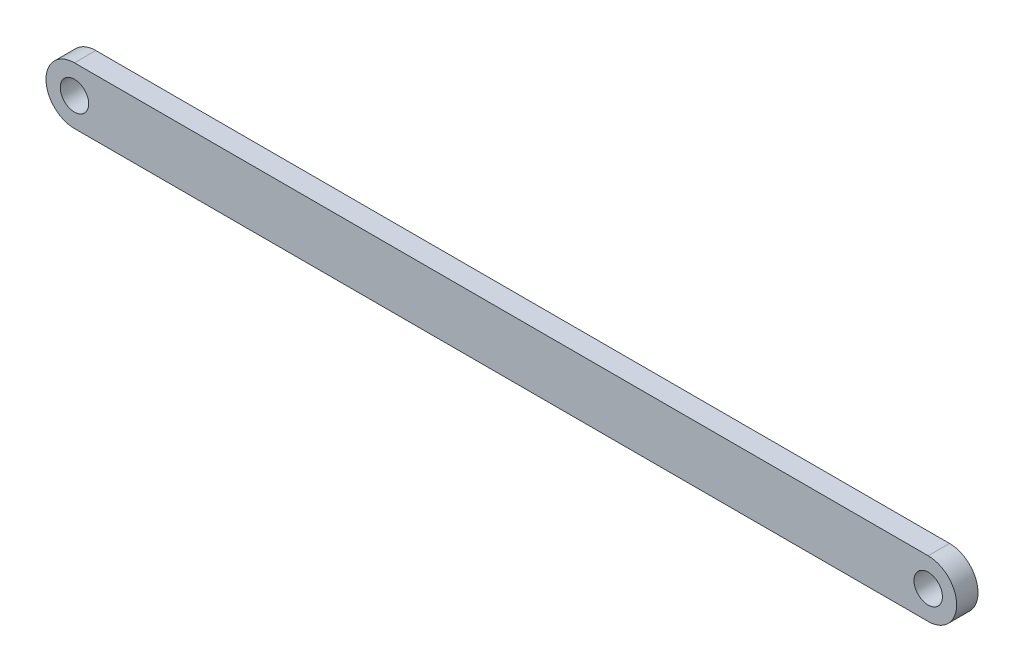
SolidWorks part; units mm, degrees
material "Zoltek Panex 33"
ref_plane "前视基准面" through (0, 0, 0) normal (0, 0, 1) x (1, 0, 0)
ref_plane "上视基准面" through (0, 0, 0) normal (0, 1, 0) x (1, 0, 0)
ref_plane "右视基准面" through (0, 0, 0) normal (1, 0, 0) x (0, 0, -1)
sketch "草图1" plane through (0, 0, 0) normal (0, 0, 1) x (1, 0, 0)
  line L1 (0, 0) -> (60, 0) construction
  line L2 (0, 2) -> (60, 2)
  line L3 (0, -2) -> (60, -2)
  arc A1 (0, 2) -> (0, -2) centre (0, 0) ccw
  arc A2 (60, -2) -> (60, 2) centre (60, 0) ccw
  circle A3 centre (60, 0) radius 1
  circle A4 centre (0, 0) radius 1
  point P6 (30, 0)
  dimension "D1" = 2
  dimension "D3" = 2
  dimension "D4" = 2
  dimension "D2" = 60
extrude "凸台-拉伸1" add sketch "草图1" along normal blind 1.5
